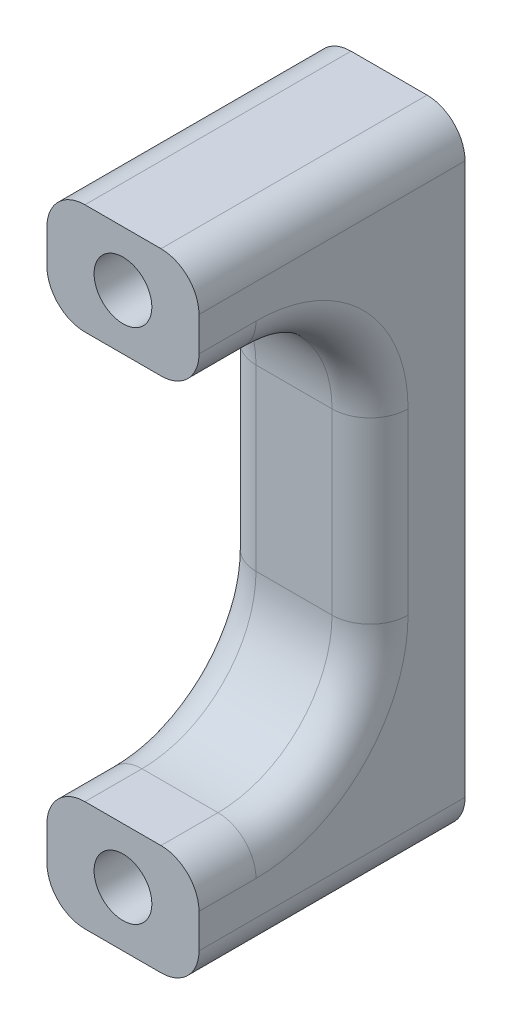
SolidWorks part; units mm, degrees
ref_plane "Front Plane" through (0, 0, 0) normal (0, 0, 1) x (1, 0, 0)
ref_plane "Top Plane" through (0, 0, 0) normal (0, 1, 0) x (1, 0, 0)
ref_plane "Right Plane" through (0, 0, 0) normal (1, 0, 0) x (0, 0, -1)
sketch "Sketch1" plane through (0, 0, 0) normal (0, 0, 1) x (1, 0, 0)
  line L1 (0, 0) -> (10.16, 0)
  line L2 (0, 0) -> (0, 41.91)
  line L3 (0, 41.91) -> (10.16, 41.91)
  line L4 (10.16, 0) -> (10.16, 41.91)
  dimension "D1" = 41.91
  dimension "D2" = 10.16
extrude "Boss-Extrude1" add sketch "Sketch1" along normal blind 17.78
ref_plane "Plane1" through (0, 20.955, 0) normal (0, 1, 0) x (1, 0, 0)
ref_plane "Plane2" through (5.08, 0, 0) normal (1, 0, 0) x (0, 0, -1)
sketch "Sketch2" plane through (0, 0, 17.78) normal (0, 0, 1) x (1, 0, 0)
  line L0 (0, 41.91) -> (0, 0) construction
  line L1 (0, 34.544) -> (10.16, 34.544)
  line L2 (0, 34.544) -> (0, 7.366)
  line L3 (0, 7.366) -> (10.16, 7.366)
  line L4 (10.16, 34.544) -> (10.16, 7.366)
  line L5 (10.16, 0) -> (10.16, 41.91) construction
  line L6 (2.794, 20.955) -> (-2.794, 20.955) construction
  point P10 (10.16, 20.955)
  dimension "D1" = 27.178
extrude "Cut-Extrude1" cut sketch "Sketch2" against normal offset from surface (11.43 mm away) 6.35 up to face at (5.08, 20.955, 0)
ref_plane "Plane3" through (0, 38.227, 0) normal (0, 1, 0) x (1, 0, 0)
ref_plane "Plane4" through (0, 3.683, 0) normal (0, 1, 0) x (1, 0, 0)
hole_wizard "#24 (0.152) Diameter Hole1" positions "Sketch3" profile "Sketch4" hole size "#24" standard "ANSI Inch" end condition up to next
sketch "Sketch3" plane through (0, 0, 17.78) normal (0, 0, 1) x (1, 0, 0)
  line L3 (5.08, -7.15) -> (5.08, 7.15) construction
  line L4 (2.794, 3.683) -> (-2.794, 3.683) construction
  line L5 (2.794, 38.227) -> (-2.794, 38.227) construction
  point P0 (5.08, 3.683)
  point P2 (5.08, 38.227)
sketch "Sketch4" plane through (5.08, 3.683, 17.78) normal (1, 0, 0) x (0, -1, 0)
  line L0 (0, 0) -> (0, 17.78)
  line L1 (0, 17.78) -> (1.9304, 17.78)
  line L2 (1.9304, 17.78) -> (1.9304, 0)
  line L5 (1.9304, 0) -> (0, 0)
  line L11 (0, -6.35) -> (0, 107.95) construction
  dimension "Thru Hole Dia." = 3.8608
  dimension "Thru Hole Depth" = 17.78
fillet "Fillet1" radius 7.62 2 edges at (5.08, 7.366, 6.35) (5.08, 34.544, 6.35)
fillet "Fillet2" radius 2.54 14 edges at (0, 7.366, 15.875) (0, 9.5978, 8.5818) (0, 20.955, 6.35) (0, 32.3122, 8.5818) (10.16, 7.366, 15.875) (10.16, 9.5978, 8.5818) (10.16, 20.955, 6.35) (10.16, 32.3122, 8.5818) (0, 0, 8.89) (10.16, 0, 8.89) (10.16, 41.91, 8.89) (0, 41.91, 8.89) (0, 34.544, 15.875) (10.16, 34.544, 15.875)
